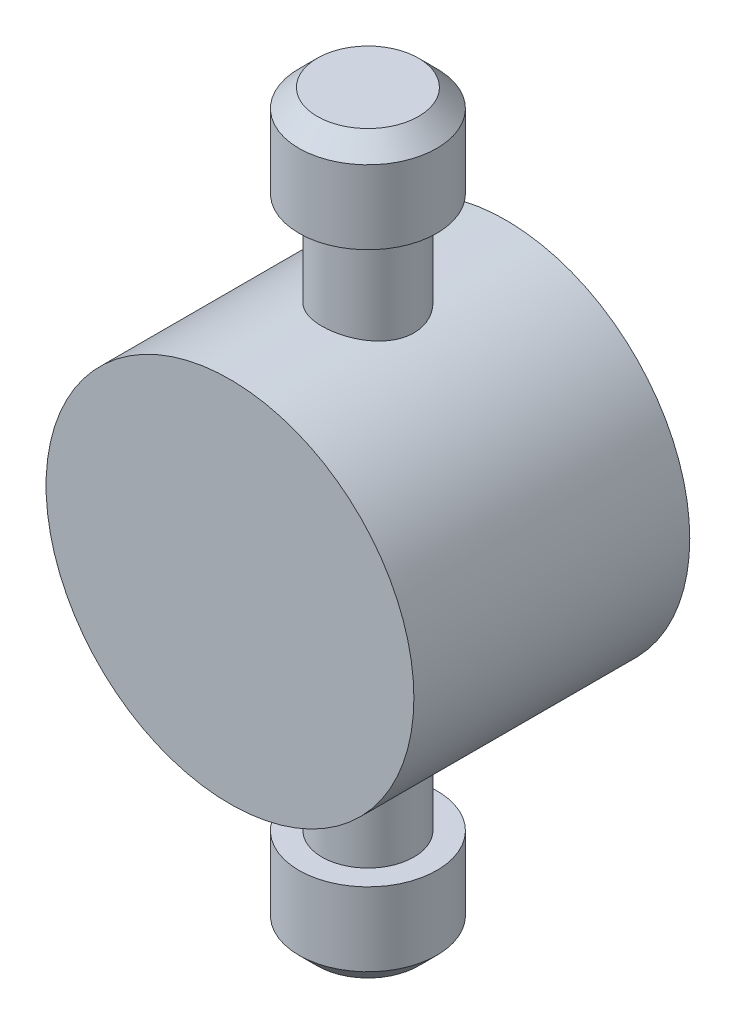
SolidWorks part; units mm, degrees
ref_plane "Ön Düzlem" through (0, 0, 0) normal (0, 0, 1) x (1, 0, 0)
ref_plane "Üst Düzlem" through (0, 0, 0) normal (0, 1, 0) x (1, 0, 0)
ref_plane "Sağ Düzlem" through (0, 0, 0) normal (1, 0, 0) x (0, 0, -1)
sketch "Sketch1" plane through (0, 0, 0) normal (0, 0, 1) x (1, 0, 0)
  circle A0 centre (0, 0) radius 20
  dimension "D1" = 40
extrude "Boss-Extrude1" add sketch "Sketch1" along normal mid plane 30
ref_plane "Plane1" through (0, 40, 0) normal (0, 1, 0) x (1, 0, 0)
sketch "Sketch2" plane through (0, 40, 0) normal (0, 1, 0) x (1, 0, 0)
  circle A0 centre (0, 0) radius 7.5
  dimension "D1" = 15
extrude "Boss-Extrude2" add sketch "Sketch2" against normal blind 10 separate body
sketch "Sketch3" plane through (0, 30, 0) normal (0, -1, 0) x (1, 0, 0)
  circle A0 centre (0, 0) radius 5
  dimension "D1" = 10
extrude "Boss-Extrude3" add sketch "Sketch3" along normal up to surface (10 mm away)
chamfer "Chamfer1" distance 2 angle 45 1 edges at (0, 40, 7.5)
mirror "Mirror21" about plane through (0, 0, 0) normal (0, 1, 0) of bodies 103
sketch "Sketch4" plane through (0, 0, -15) normal (0, 0, -1) x (-1, 0, 0)
  circle A0 centre (0, 0) radius 5
  dimension "D1" = 10
extrude "Cut-Extrude1" cut sketch "Sketch4" against normal blind 10
